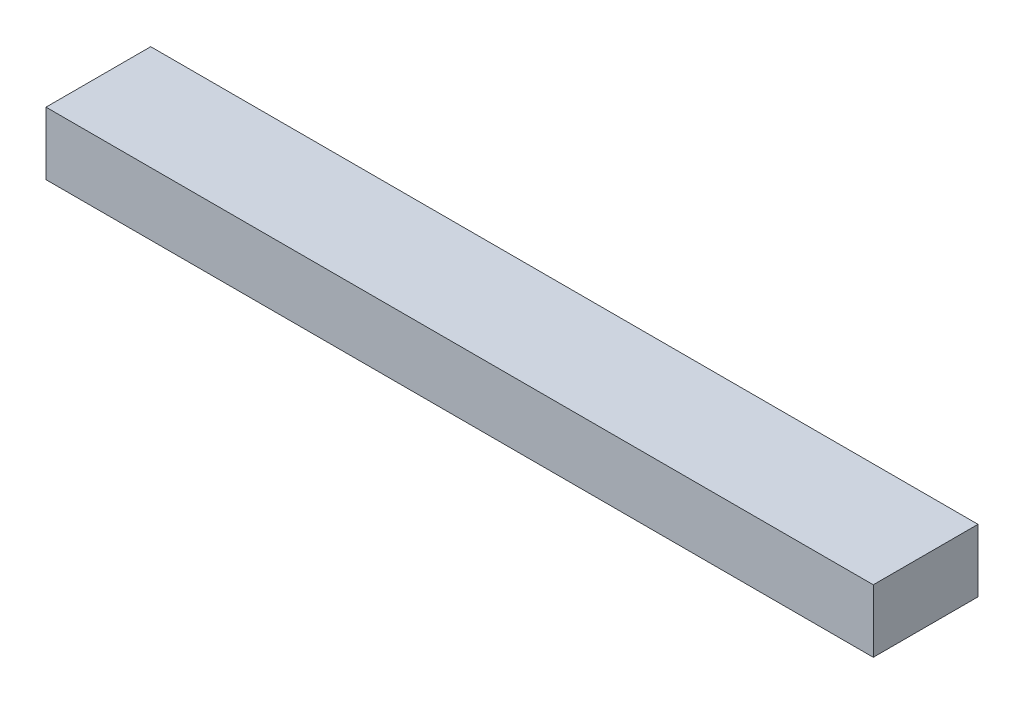
SolidWorks part; units mm, degrees
material "Pine"
ref_plane "Front Plane" through (0, 0, 0) normal (0, 0, 1) x (1, 0, 0)
ref_plane "Top Plane" through (0, 0, 0) normal (0, 1, 0) x (1, 0, 0)
ref_plane "Right Plane" through (0, 0, 0) normal (1, 0, 0) x (0, 0, -1)
sketch "Sketch1" plane through (0, 0, 0) normal (0, 1, 0) x (1, 0, 0)
  line L1 (0, -10) -> (79, -10)
  line L2 (0, -10) -> (0, -20)
  line L3 (0, -20) -> (79, -20)
  line L4 (79, -10) -> (79, -20)
  dimension "D1" = 10
extrude "Boss-Extrude1" add sketch "Sketch1" along normal blind 6 contours L3 L4 L1 L2
